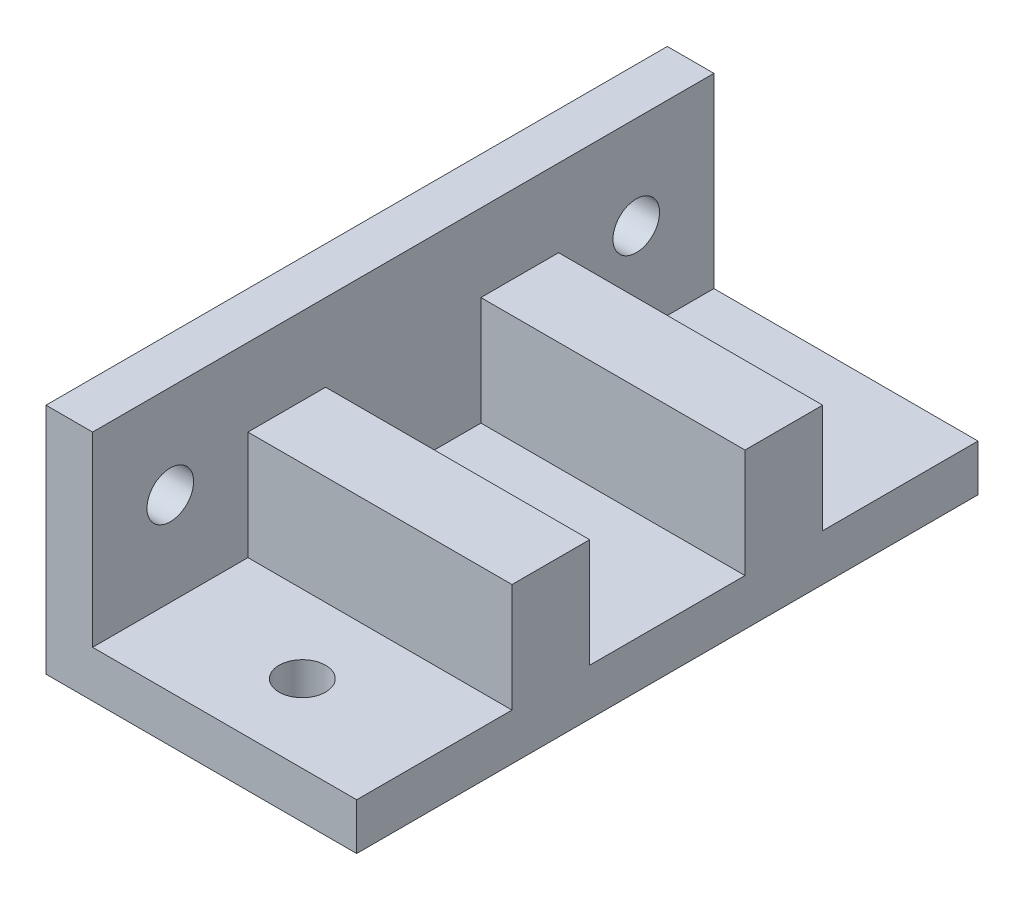
SolidWorks part; units mm, degrees
material "POM 乙缩醛共聚物"
ref_plane "前视基准面" through (0, 0, 0) normal (0, 0, 1) x (1, 0, 0)
ref_plane "上视基准面" through (0, 0, 0) normal (0, 1, 0) x (1, 0, 0)
ref_plane "右视基准面" through (0, 0, 0) normal (1, 0, 0) x (0, 0, -1)
sketch "草图1" plane through (0, 0, 0) normal (0, 0, 1) x (1, 0, 0)
  line L0 (0, 0) -> (0, 15)
  line L1 (0, 15) -> (3, 15)
  line L2 (3, 15) -> (3, 3)
  line L3 (3, 3) -> (20, 3)
  line L4 (20, 3) -> (20, 0)
  line L5 (20, 0) -> (0, 0)
  dimension "D1" = 20
  dimension "D2" = 15
  dimension "D3" = 3
  dimension "D4" = 3
extrude "凸台-拉伸1" add sketch "草图1" along normal blind 40
sketch "草图3" plane through (3, 0, 0) normal (1, 0, 0) x (0, 0, -1)
  line L0 (-20, 15) -> (-20, 3) construction
  line L1 (-40, 15) -> (0, 15) construction
  line L2 (-40, 3) -> (0, 3) construction
  line L3 (-40, 0) -> (0, 0) construction
  circle A1 centre (-35, 9) radius 1.5
  circle A2 centre (-5, 9) radius 1.5
  dimension "D1" = 9
  dimension "D2" = 3
  dimension "D3" = 15
extrude "切除-拉伸1" cut sketch "草图3" against normal through all
sketch "草图4" plane through (0, 3, 0) normal (0, 1, 0) x (1, 0, 0)
  line L0 (3, -20) -> (20, -20) construction
  line L1 (3, -40) -> (3, 0) construction
  line L2 (20, -40) -> (20, 0) construction
  line L3 (0, -40) -> (0, 0) construction
  circle A0 centre (11.5, -20) radius 1.5
  circle A1 centre (11.5, -35) radius 1.5
  circle A2 centre (11.5, -5) radius 1.5
  dimension "D1" = 11.5
  dimension "D3" = 3
  dimension "D2" = 15
extrude "切除-拉伸2" cut sketch "草图4" against normal through all
sketch "草图5" plane through (0, 3, 0) normal (0, 1, 0) x (1, 0, 0)
  line L0 (3, -40) -> (3, 0) construction
  line L1 (3, -30) -> (20, -30)
  line L2 (3, -30) -> (3, -25)
  line L3 (3, -25) -> (20, -25)
  line L4 (20, -30) -> (20, -25)
  line L5 (20, -40) -> (20, 0) construction
  line L6 (3, -20) -> (20, -20) construction
  line L7 (20, -10) -> (20, -15)
  line L8 (3, -15) -> (20, -15)
  line L9 (3, -10) -> (3, -15)
  line L10 (3, -10) -> (20, -10)
  dimension "D1" = 5
  dimension "D2" = 5
extrude "凸台-拉伸2" add sketch "草图5" along normal blind 7
